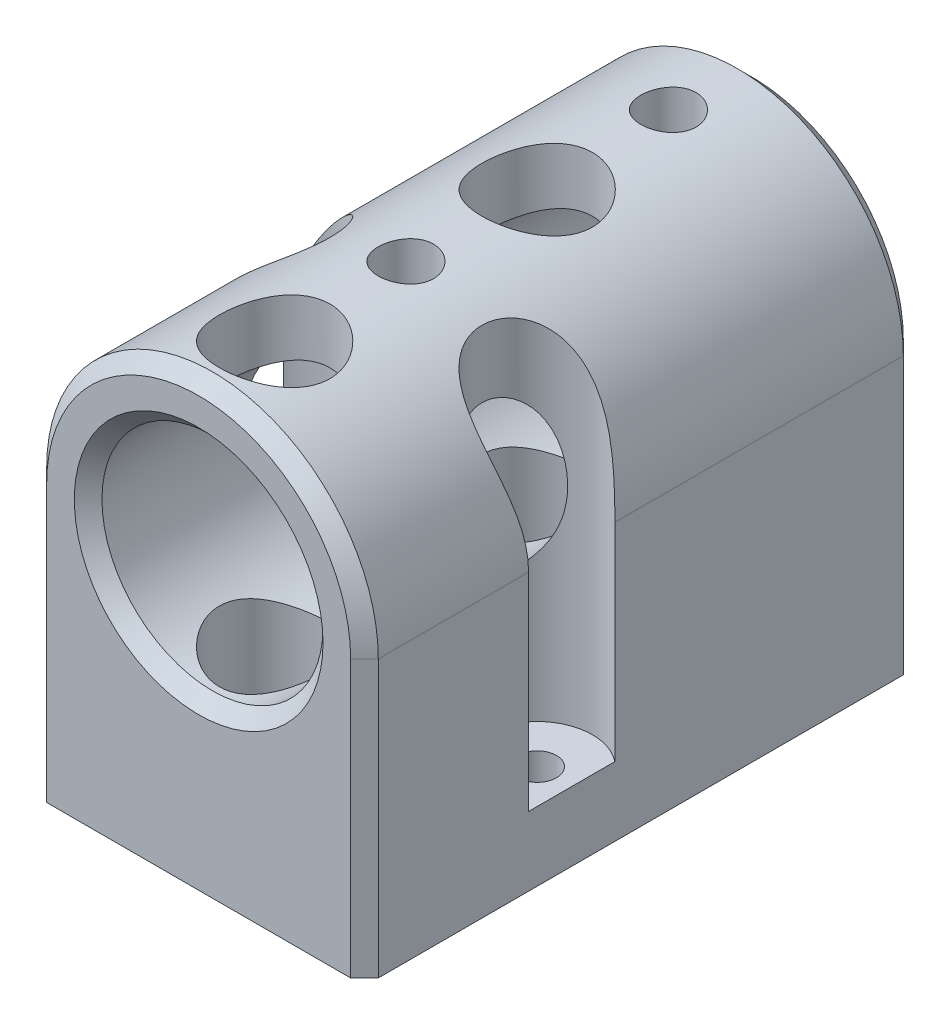
SolidWorks part; units mm, degrees
ref_plane "Front Plane" through (0, 0, 0) normal (0, 0, 1) x (1, 0, 0)
ref_plane "Top Plane" through (0, 0, 0) normal (0, 1, 0) x (1, 0, 0)
ref_plane "Right Plane" through (0, 0, 0) normal (1, 0, 0) x (0, 0, -1)
sketch "Sketch1" plane through (0, 0, 0) normal (0, 0, 1) x (1, 0, 0)
  line L0 (-12, 0) -> (-12, -20)
  line L1 (-12, -20) -> (12, -20)
  line L2 (12, -20) -> (12, 0)
  circle A0 centre (0, 0) radius 8
  arc A1 (12, 0) -> (-12, 0) centre (0, 0) ccw
  dimension "D1" = 16
  dimension "D2" = 24
  dimension "D3" = 20
extrude "Boss-Extrude1" add sketch "Sketch1" along normal blind 40
sketch "Sketch2" plane through (0, -20, 0) normal (0, -1, 0) x (1, 0, 0)
  line L0 (-12, 40) -> (12, 40) construction
  circle A0 centre (0, 25) radius 9.5 construction
  circle A1 centre (-9.5, 25) radius 1.4
  circle A2 centre (0, 34.5) radius 1.4
  circle A3 centre (9.5, 25) radius 1.4
  circle A4 centre (0, 15.5) radius 1.4
  dimension "D1" = 19
  dimension "D2" = 2.8
  dimension "D4" = 15
  dimension "D3" = 4
extrude "Cut-Extrude1" cut sketch "Sketch2" against normal through all both and the other way through all
sketch "Sketch4" plane through (0, 0, 0) normal (0, 1, 0) x (1, 0, 0)
  circle A0 centre (0, -15.5) radius 4
  circle A1 centre (0, -34.5) radius 4
  circle A2 centre (-9.5, -25) radius 4
  circle A3 centre (9.5, -25) radius 4
  dimension "D1" = 8
  dimension "D2" = 8
  dimension "D3" = 8
  dimension "D4" = 8
extrude "Cut-Extrude3" cut sketch "Sketch4" against normal blind 15 and the other way through all
sketch "Sketch5" plane through (0, 0, 0) normal (0, 1, 0) x (1, 0, 0)
  line L0 (12, 0) -> (-12, 0) construction
  circle A0 centre (0, -6) radius 2
  circle A1 centre (0, -25) radius 2
  dimension "D1" = 4
  dimension "D2" = 4
  dimension "D3" = 25
  dimension "D4" = 6
  dimension "D5" = 19
extrude "Cut-Extrude4" cut sketch "Sketch5" along normal blind 30
chamfer "Chamfer1" distance 1 angle 45 8 edges at (8, 0, 40) (8, 0, 0) (12, -10, 0) (0, 12, 0) (-12, -10, 0) (12, -10, 40) (0, 12, 40) (-12, -10, 40)
